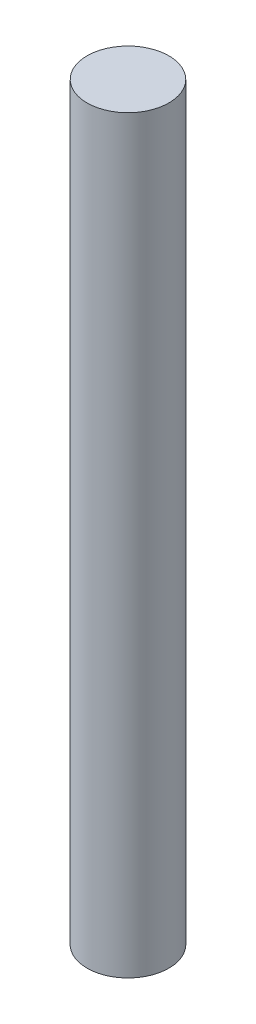
SolidWorks part; units mm, degrees
material "1023 Carbon Steel Sheet (SS)"
ref_plane "Front Plane" through (0, 0, 0) normal (0, 0, 1) x (1, 0, 0)
ref_plane "Top Plane" through (0, 0, 0) normal (0, 1, 0) x (1, 0, 0)
ref_plane "Right Plane" through (0, 0, 0) normal (1, 0, 0) x (0, 0, -1)
sketch "Sketch1" plane through (0, 0, 0) normal (0, 1, 0) x (1, 0, 0)
  circle A0 centre (0, 0) radius 3
  dimension "D1" = 6
extrude "Boss-Extrude1" add sketch "Sketch1" along normal blind 55
